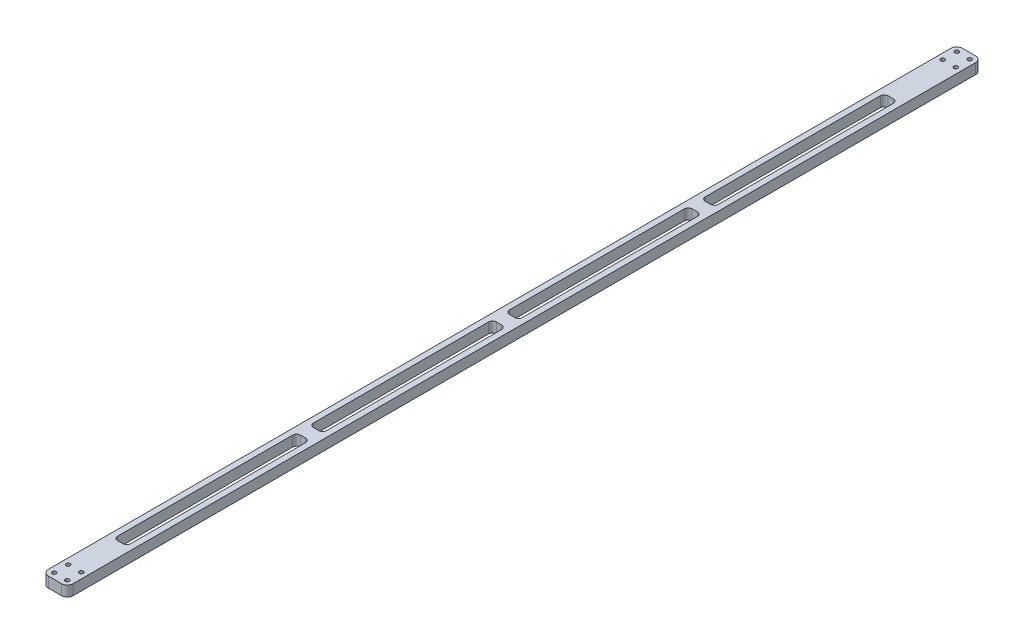
SolidWorks part; units mm, degrees
ref_plane "前视基准面" through (0, 0, 0) normal (0, 0, 1) x (1, 0, 0)
ref_plane "上视基准面" through (0, 0, 0) normal (0, 1, 0) x (1, 0, 0)
ref_plane "右视基准面" through (0, 0, 0) normal (1, 0, 0) x (0, 0, -1)
sketch "草图1" plane through (0, 0, 0) normal (0, 1, 0) x (1, 0, 0)
  line L0 (19, 350) -> (303.7566, 350) construction
  line L1 (4.5, 0) -> (14.5, 0)
  line L2 (0, 4.5) -> (0, 695.5)
  line L3 (4.5, 700) -> (14.5, 700)
  line L4 (19, 4.5) -> (19, 695.5)
  circle A0 centre (4.5, 4.5) radius 1.5
  circle A1 centre (14.5, 4.5) radius 1.5
  circle A2 centre (4.5, 15.0866) radius 1.5
  circle A3 centre (14.5, 15.0866) radius 1.5
  circle A4 centre (14.5, 684.9134) radius 1.5
  circle A5 centre (4.5, 684.9134) radius 1.5
  circle A6 centre (14.5, 695.5) radius 1.5
  circle A7 centre (4.5, 695.5) radius 1.5
  arc A8 (4.5, 700) -> (0, 695.5) centre (4.5, 695.5) ccw
  arc A9 (14.5, 700) -> (19, 695.5) centre (14.5, 695.5) cw
  arc A10 (4.5, 0) -> (0, 4.5) centre (4.5, 4.5) cw
  arc A11 (14.5, 0) -> (19, 4.5) centre (14.5, 4.5) ccw
  point P27 (19, 700)
  point P30 (0, 0)
  point P33 (19, 0)
  dimension "D3" = 3
  dimension "D8" = 4.5
  dimension "D9" = 4.5
  dimension "D10" = 4.5
  dimension "D1" = 19
  dimension "D2" = 700
  dimension "D4" = 4.5
  dimension "D5" = 4.5
  dimension "D6" = 2
  dimension "D7" = 2
extrude "凸台-拉伸1" add sketch "草图1" along normal blind 8
sketch "草图5" plane through (0, 8, 0) normal (0, 1, 0) x (1, 0, 0)
  line L0 (0, 695.5) -> (0, 4.5) construction
  line L1 (7.5, 50) -> (11.5, 50)
  line L2 (4.5, 53) -> (4.5, 187)
  line L3 (14.5, 203) -> (14.5, 337)
  line L4 (14.5, 53) -> (14.5, 187)
  line L5 (4.5, 0) -> (14.5, 0) construction
  line L6 (7.5, 190) -> (11.5, 190)
  line L7 (4.5, 203) -> (4.5, 337)
  line L8 (7.5, 340) -> (11.5, 340)
  line L9 (7.5, 200) -> (11.5, 200)
  line L10 (14.5, 353) -> (14.5, 487)
  line L11 (4.5, 353) -> (4.5, 487)
  line L12 (7.5, 490) -> (11.5, 490)
  line L13 (7.5, 350) -> (11.5, 350)
  line L14 (14.5, 503) -> (14.5, 637)
  line L15 (4.5, 503) -> (4.5, 637)
  line L16 (7.5, 640) -> (11.5, 640)
  line L17 (7.5, 500) -> (11.5, 500)
  arc A0 (14.5, 637) -> (11.5, 640) centre (11.5, 637) ccw
  arc A1 (4.5, 637) -> (7.5, 640) centre (7.5, 637) cw
  arc A2 (14.5, 503) -> (11.5, 500) centre (11.5, 503) cw
  arc A3 (4.5, 503) -> (7.5, 500) centre (7.5, 503) ccw
  arc A4 (14.5, 487) -> (11.5, 490) centre (11.5, 487) ccw
  arc A5 (4.5, 487) -> (7.5, 490) centre (7.5, 487) cw
  arc A6 (14.5, 353) -> (11.5, 350) centre (11.5, 353) cw
  arc A7 (4.5, 353) -> (7.5, 350) centre (7.5, 353) ccw
  arc A8 (14.5, 337) -> (11.5, 340) centre (11.5, 337) ccw
  arc A9 (4.5, 337) -> (7.5, 340) centre (7.5, 337) cw
  arc A10 (14.5, 203) -> (11.5, 200) centre (11.5, 203) cw
  arc A11 (11.5, 190) -> (14.5, 187) centre (11.5, 187) cw
  arc A12 (7.5, 190) -> (4.5, 187) centre (7.5, 187) ccw
  arc A13 (11.5, 50) -> (14.5, 53) centre (11.5, 53) ccw
  arc A14 (4.5, 203) -> (7.5, 200) centre (7.5, 203) ccw
  arc A15 (7.5, 50) -> (4.5, 53) centre (7.5, 53) cw
  point P48 (14.5, 50)
  point P53 (4.5, 50)
  dimension "D6" = 3
  dimension "D1" = 10
  dimension "D2" = 4.5
  dimension "D3" = 4
  dimension "D4" = 50
  dimension "D5" = 140
extrude "切除-拉伸2" cut sketch "草图5" against normal through all
